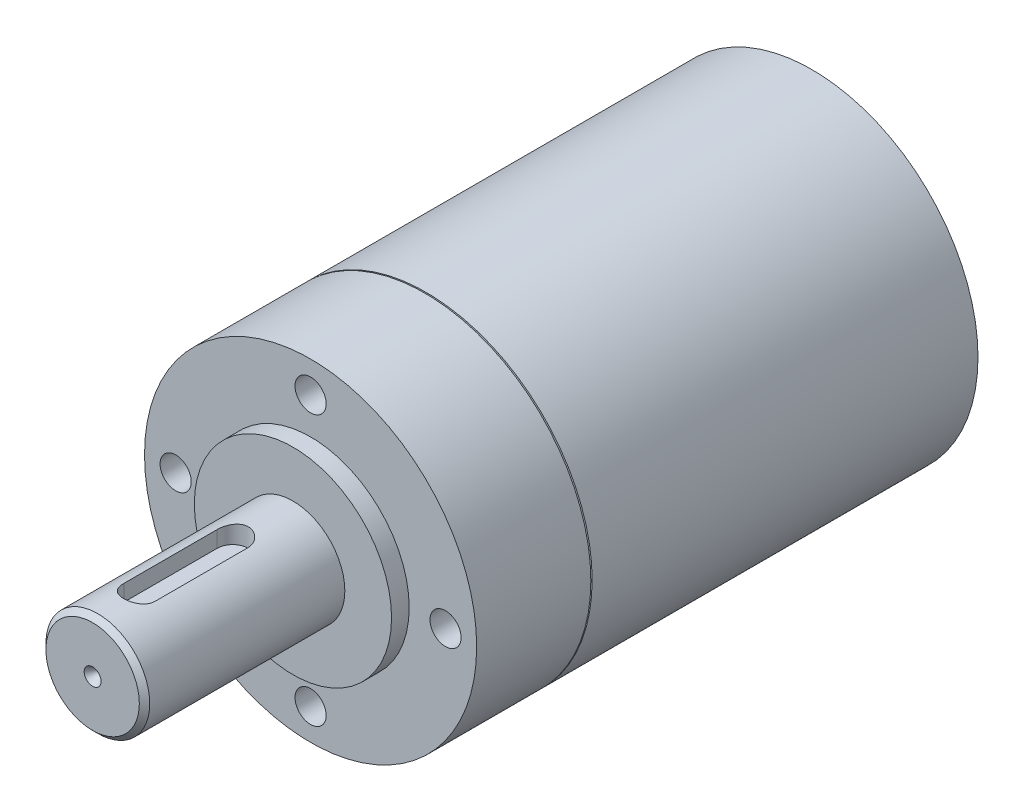
SolidWorks part; units mm, degrees
material "AISI 1020"
ref_plane "前视基准面" through (0, 0, 0) normal (0, 0, 1) x (1, 0, 0)
ref_plane "上视基准面" through (0, 0, 0) normal (0, 1, 0) x (1, 0, 0)
ref_plane "右视基准面" through (0, 0, 0) normal (1, 0, 0) x (0, 0, -1)
sketch "草图8" plane through (0, 0, 0) normal (0, 0, 1) x (1, 0, 0)
  circle A0 centre (0, 0) radius 16
extrude "凸台-拉伸1" add sketch "草图8" along normal blind 48.3
sketch "草图9" plane through (0, 0, 48.3) normal (0, 0, 1) x (1, 0, 0)
  circle A0 centre (0, 0) radius 9.5
extrude "凸台-拉伸2" add sketch "草图9" along normal blind 1.7
sketch "草图10" plane through (0, 0, 50) normal (0, 0, 1) x (1, 0, 0)
  circle A0 centre (0, 0) radius 5
extrude "凸台-拉伸3" add sketch "草图10" along normal blind 19.3
sketch "草图11" plane through (0, 0, 69.3) normal (0, 0, 1) x (1, 0, 0)
  circle A0 centre (0, 0) radius 0.8133
extrude "切除-拉伸7" cut sketch "草图11" against normal blind 3 draft 32
ref_plane "基准面5" through (0, 3.2, 0) normal (0, 1, 0) x (1, 0, 0)
sketch "草图12" plane through (0, 3.2, 0) normal (0, 1, 0) x (1, 0, 0)
  line L0 (0, -69.3) -> (0, -64.8) construction
  line L1 (-5, -69.3) -> (5, -69.3) construction
  line L2 (0, -64.8) -> (0, -55.8) construction
  line L3 (-1.5, -64.8) -> (-1.5, -55.8)
  line L4 (1.5, -64.8) -> (1.5, -55.8)
  arc A0 (-1.5, -64.8) -> (1.5, -64.8) centre (0, -64.8) ccw
  arc A1 (1.5, -55.8) -> (-1.5, -55.8) centre (0, -55.8) ccw
  point P5 (0, -60.3)
  dimension "D1" = 4.5
  dimension "D2" = 1.5
  dimension "D3" = 9
extrude "切除-拉伸8" cut sketch "草图12" along normal blind 3
sketch "草图13" plane through (0, 0, 48.3) normal (0, 0, 1) x (1, 0, 0)
  circle A0 centre (0, 0) radius 13 construction
  circle A1 centre (0, 13) radius 1.5
  circle A2 centre (-13, 0) radius 1.5
  circle A3 centre (0, -13) radius 1.5
  circle A4 centre (13, 0) radius 1.5
  dimension "D1" = 26
  dimension "D2" = 3
extrude "切除-拉伸9" cut sketch "草图13" against normal blind 6
sketch "草图14" plane through (0, 0, 0) normal (0, 0, -1) x (-1, 0, 0)
  circle A0 centre (0, 0) radius 8
extrude "切除-拉伸10" cut sketch "草图14" against normal blind 1.2
sketch "草图15" plane through (0, 0, 0) normal (0, 0, -1) x (-1, 0, 0)
  circle A0 centre (0, 0) radius 2.5
extrude "切除-拉伸11" cut sketch "草图15" against normal blind 20
sketch "草图16" plane through (0, 0, 0) normal (0, 0, -1) x (-1, 0, 0)
  circle A0 centre (0, 0) radius 11 construction
  circle A1 centre (0, 11) radius 1.5
  circle A2 centre (11, 0) radius 1.5
  circle A3 centre (0, -11) radius 1.5
  circle A4 centre (-11, 0) radius 1.5
extrude "切除-拉伸12" cut sketch "草图16" against normal blind 4
sketch "草图17" plane through (0, 0, 0) normal (0, 1, 0) x (1, 0, 0)
  line L0 (-16, -48.3) -> (16, -48.3) construction
  line L1 (17.2076, -37.3) -> (15.8202, -37.3)
  line L2 (17.2076, -37.3) -> (17.2076, -37.1732)
  line L3 (17.2076, -37.1732) -> (15.8202, -37.1732)
  line L4 (15.8202, -37.3) -> (15.8202, -37.1732)
  dimension "D1" = 11
revolve "切除-旋转1" cut sketch "草图17" angle 360 about axis through (0, 0, 69.3) along (0, 0, -1)
chamfer "倒角1" distance 0.5 angle 45 1 edges at (5, 0, 69.3)
